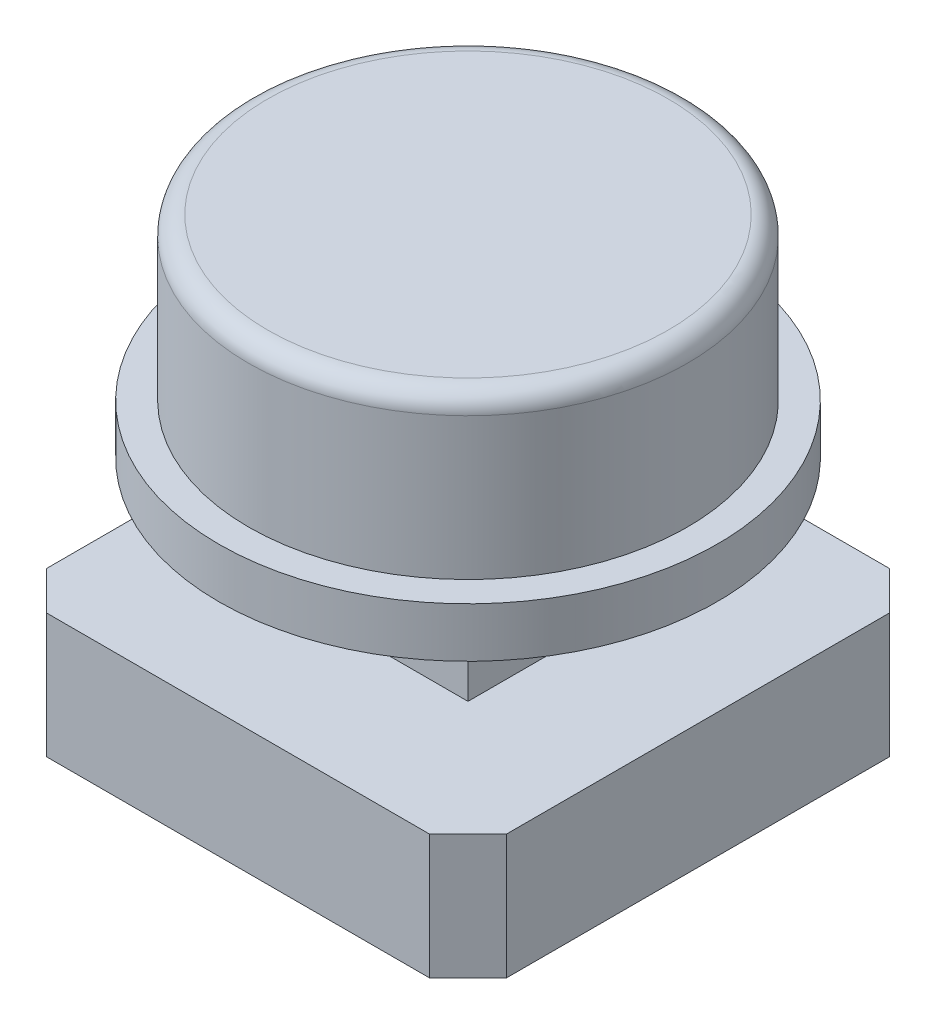
SolidWorks part; units mm, degrees
ref_plane "Front Plane" through (0, 0, 0) normal (0, 0, 1) x (1, 0, 0)
ref_plane "Top Plane" through (0, 0, 0) normal (0, 1, 0) x (1, 0, 0)
ref_plane "Right Plane" through (0, 0, 0) normal (1, 0, 0) x (0, 0, -1)
sketch "Sketch1" plane through (0, 0, 0) normal (0, 1, 0) x (1, 0, 0)
  line L1 (6, -6) -> (-6, -6)
  line L2 (6, -6) -> (6, 6)
  line L3 (6, 6) -> (-6, 6)
  line L4 (-6, -6) -> (-6, 6)
  line L5 (6, -6) -> (-6, 6) construction
  line L6 (6, 6) -> (-6, -6) construction
  point P0 (0, 0)
  dimension "D1" = 12
  dimension "D2" = 12
extrude "Boss-Extrude1" add sketch "Sketch1" along normal blind 3.25
chamfer "Chamfer1" distance 1 angle 45 4 edges at (-6, 1.625, -6) (6, 1.625, -6) (6, 1.625, 6) (-6, 1.625, 6)
sketch "Sketch2" plane through (0, 3.25, 0) normal (0, 1, 0) x (1, 0, 0)
  line L1 (2.5, -2.5) -> (-2.5, -2.5)
  line L2 (2.5, -2.5) -> (2.5, 2.5)
  line L3 (2.5, 2.5) -> (-2.5, 2.5)
  line L4 (-2.5, -2.5) -> (-2.5, 2.5)
  line L5 (2.5, -2.5) -> (-2.5, 2.5) construction
  line L6 (2.5, 2.5) -> (-2.5, -2.5) construction
  point P0 (0, 0)
  dimension "D1" = 5
  dimension "D2" = 5
extrude "Boss-Extrude2" add sketch "Sketch2" along normal blind 3
sketch "Sketch3" plane through (0, 6.25, 0) normal (0, 1, 0) x (1, 0, 0)
  circle A0 centre (0, 0) radius 6.5
  dimension "D1" = 13
extrude "Boss-Extrude3" add sketch "Sketch3" along normal blind 5.5
sketch "Sketch4" plane through (0, 11.75, 0) normal (0, 1, 0) x (1, 0, 0)
  circle A0 centre (0, 0) radius 6.5
  circle A1 centre (0, 0) radius 5.725
  circle A2 centre (0, 0) radius 6.5 construction
  dimension "D1" = 11.45
extrude "Cut-Extrude1" cut sketch "Sketch4" against normal blind 4.2
fillet "Fillet1" radius 0.5 1 edges at (0, 11.75, 5.725)
